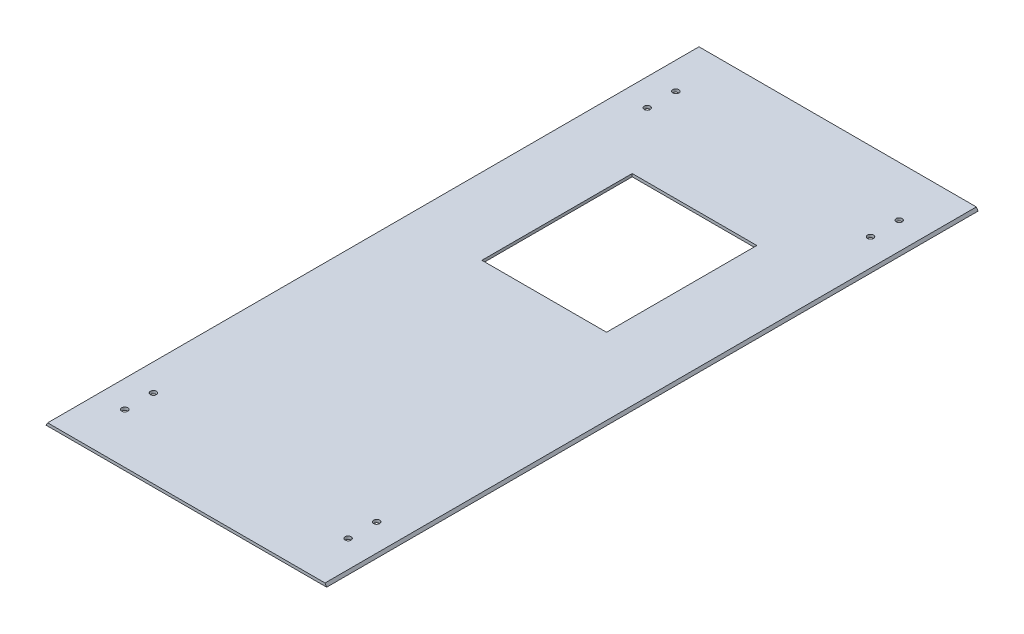
SolidWorks part; units mm, degrees
ref_plane "前视基准面" through (0, 0, 0) normal (0, 0, 1) x (1, 0, 0)
ref_plane "上视基准面" through (0, 0, 0) normal (0, 1, 0) x (1, 0, 0)
ref_plane "右视基准面" through (0, 0, 0) normal (1, 0, 0) x (0, 0, -1)
other "Configuration Table"
sketch "草图2" plane through (0, 0, 0) normal (0, 0, 1) x (1, 0, 0)
  line L0 (-98, -1) -> (-96.8453, 1)
  line L1 (-98, -1) -> (98.07, -1)
  line L3 (-96.8453, 1) -> (96.9153, 1)
  line L5 (-98, -1) -> (96.9217, 0.989) construction
  line L6 (-96.8525, 0.9876) -> (98.07, -1) construction
  line L7 (98.07, -1) -> (96.9153, 1)
  point P0 (0, 0)
  dimension "D1" = 60
  dimension "D2" = 196.07
  dimension "D3" = 60
  dimension "D4" = 2
  dimension "D5" = 1
extrude "凸台-拉伸1" add sketch "草图2" against normal blind 455
sketch "草图3" plane through (0, -1, 0) normal (0, -1, 0) x (-1, 0, 0)
  line L0 (98, 0) -> (-98.07, 0) construction
  line L1 (98, 455) -> (98, 0) construction
  line L2 (0, 0) -> (0, 458.5279) construction
  line L3 (98, 227.5) -> (-98.07, 227.5) construction
  line L4 (-98.07, 455) -> (-98.07, 0) construction
  circle A0 centre (78, 35) radius 2.1
  circle A1 centre (78, 55) radius 2.1
  circle A2 centre (-78, 55) radius 2.1
  circle A3 centre (-78, 35) radius 2.1
  circle A4 centre (-78, 420) radius 2.1
  circle A5 centre (-78, 400) radius 2.1
  circle A6 centre (78, 400) radius 2.1
  circle A7 centre (78, 420) radius 2.1
  dimension "D1" = 20
  dimension "D2" = 20
  dimension "D3" = 20
  dimension "D4" = 35
extrude "切除-拉伸1" cut sketch "草图3" against normal through all
sketch "草图6" plane through (0, -1, 0) normal (0, -1, 0) x (1, 0, 0)
  line L0 (0, -455.8858) -> (0, 0) construction
sketch "草图7" plane through (0, -1, 0) normal (0, -1, 0) x (1, 0, 0)
  line L0 (-98, -455) -> (-98, 0) construction
  line L2 (-43.5, -250) -> (43.57, -250)
  line L3 (-43.5, -250) -> (-43.5, -355)
  line L4 (-43.5, -355) -> (43.57, -355)
  line L5 (43.57, -250) -> (43.57, -355)
  line L6 (98.07, -455) -> (98.07, 0) construction
  line L7 (-98, -455) -> (98.07, -455) construction
  dimension "D1" = 54.5
  dimension "D2" = 54.5
  dimension "D3" = 100
  dimension "D4" = 105
extrude "切除-拉伸2" cut sketch "草图7" against normal blind 10 contours L3 L2 L5 L4
